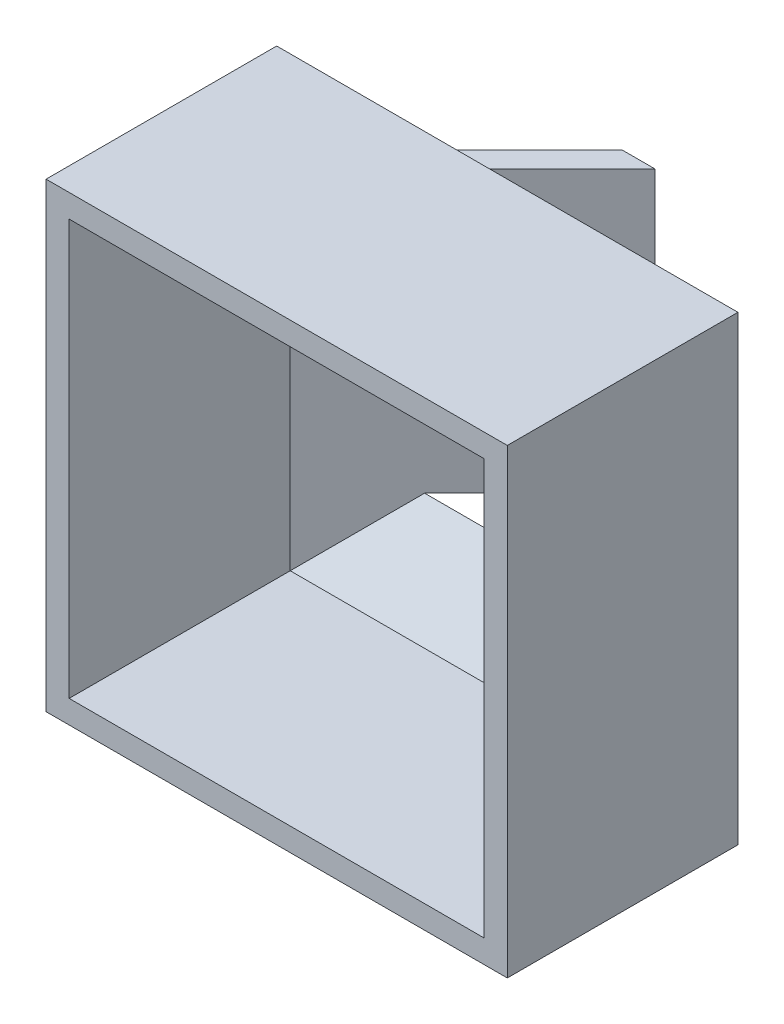
SolidWorks part; units mm, degrees
ref_plane "Front Plane" through (0, 0, 0) normal (0, 0, 1) x (1, 0, 0)
ref_plane "Top Plane" through (0, 0, 0) normal (0, 1, 0) x (1, 0, 0)
ref_plane "Right Plane" through (0, 0, 0) normal (1, 0, 0) x (0, 0, -1)
sketch "Sketch1" plane through (0, 0, 0) normal (0, 0, 1) x (1, 0, 0)
  line L1 (0, 0) -> (40, 0)
  line L2 (0, 0) -> (0, -40)
  line L3 (0, -40) -> (40, -40)
  line L4 (40, 0) -> (40, -40)
  point P4 (0, 0)
  dimension "D1" = 40
  dimension "D2" = 40
extrude "Boss-Extrude1" add sketch "Sketch1" along normal blind 25
chamfer "Chamfer1" distance 5 angle 45 1 edges at (0, -20, 0)
chamfer "Chamfer2" distance 5 angle 45 1 edges at (40, -20, 0)
chamfer "Chamfer3" distance 5 angle 45 1 edges at (20, -40, 0)
chamfer "Chamfer4" distance 5 angle 45 1 edges at (20, 0, 0)
shell "Shell1" thickness 2
sketch "Sketch7" plane through (0, 0, 0) normal (0, 0, -1) x (-1, 0, 0)
  line L0 (-32.1716, -32.1716) -> (-7.8284, -32.1716) construction
  line L1 (-7.8284, -7.8284) -> (-17.8284, -7.8284)
  line L2 (-7.8284, -7.8284) -> (-7.8284, -32.1716)
  line L3 (-7.8284, -32.1716) -> (-17.8284, -32.1716)
  line L4 (-17.8284, -7.8284) -> (-17.8284, -32.1716)
  dimension "10" = 10
extrude "Boss-Extrude6" add sketch "Sketch7" along normal blind 10 separate body
sketch "Sketch8" plane through (0, -7.8284, 0) normal (0, 1, 0) x (1, 0, 0)
  line L0 (7.8284, 0) -> (17.8284, 0)
  line L1 (17.8284, 0) -> (17.8284, 10)
  line L2 (17.8284, 10) -> (7.8284, 0)
extrude "Cut-Extrude2" cut sketch "Sketch8" against normal up to vertex (24.3431 mm away)
sketch "Sketch9" plane through (7.8284, 0, 0) normal (-1, 0, 0) x (0, 0, 1)
  line L0 (0, -32.1716) -> (0, -7.8284) construction
  line L1 (-10, -7.8284) -> (0, -7.8284)
  line L2 (-10, -7.8284) -> (-10, -32.1716)
  line L3 (-10, -32.1716) -> (0, -32.1716)
  line L4 (0, -7.8284) -> (0, -32.1716)
  line L5 (-10, -32.1716) -> (0, -32.1716) construction
sketch "Sketch11" plane through (7.8284, 0, 0) normal (-1, 0, 0) x (0, 0, 1)
  line L1 (-10, -7.8284) -> (0, -7.8284)
  line L2 (-10, -7.8284) -> (-10, -32.1716)
  line L3 (-10, -32.1716) -> (0, -32.1716)
  line L4 (0, -7.8284) -> (0, -32.1716)
extrude "Boss-Extrude8" add sketch "Sketch11" along normal up to vertex (2.8284 mm away)
sketch "Sketch13" plane through (0, -7.8284, 0) normal (0, 1, 0) x (1, 0, 0)
  line L0 (5, 0) -> (15, 10)
  line L1 (5, 10) -> (17.8284, 10) construction
  line L6 (5, 0) -> (5, 10)
  line L7 (5, 10) -> (15, 10)
  line L8 (17.8284, 10) -> (7.8284, 0) construction
extrude "Cut-Extrude4" cut sketch "Sketch13" against normal through all
